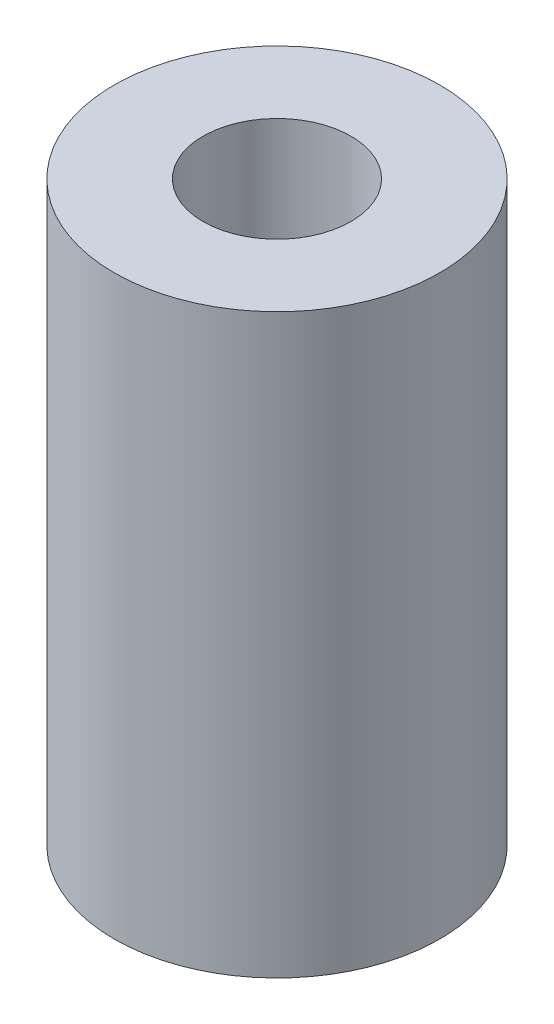
SolidWorks part; units mm, degrees
ref_plane "Front Plane" through (0, 0, 0) normal (0, 0, 1) x (1, 0, 0)
ref_plane "Top Plane" through (0, 0, 0) normal (0, 1, 0) x (1, 0, 0)
ref_plane "Right Plane" through (0, 0, 0) normal (1, 0, 0) x (0, 0, -1)
sketch "Sketch1" plane through (0, 0, 0) normal (0, 1, 0) x (1, 0, 0)
  circle A0 centre (0, 0) radius 1
  circle A1 centre (0, 0) radius 2.2
  dimension "D1" = 4.4
  dimension "D2" = 2
extrude "Boss-Extrude1" add sketch "Sketch1" along normal blind 7.8
